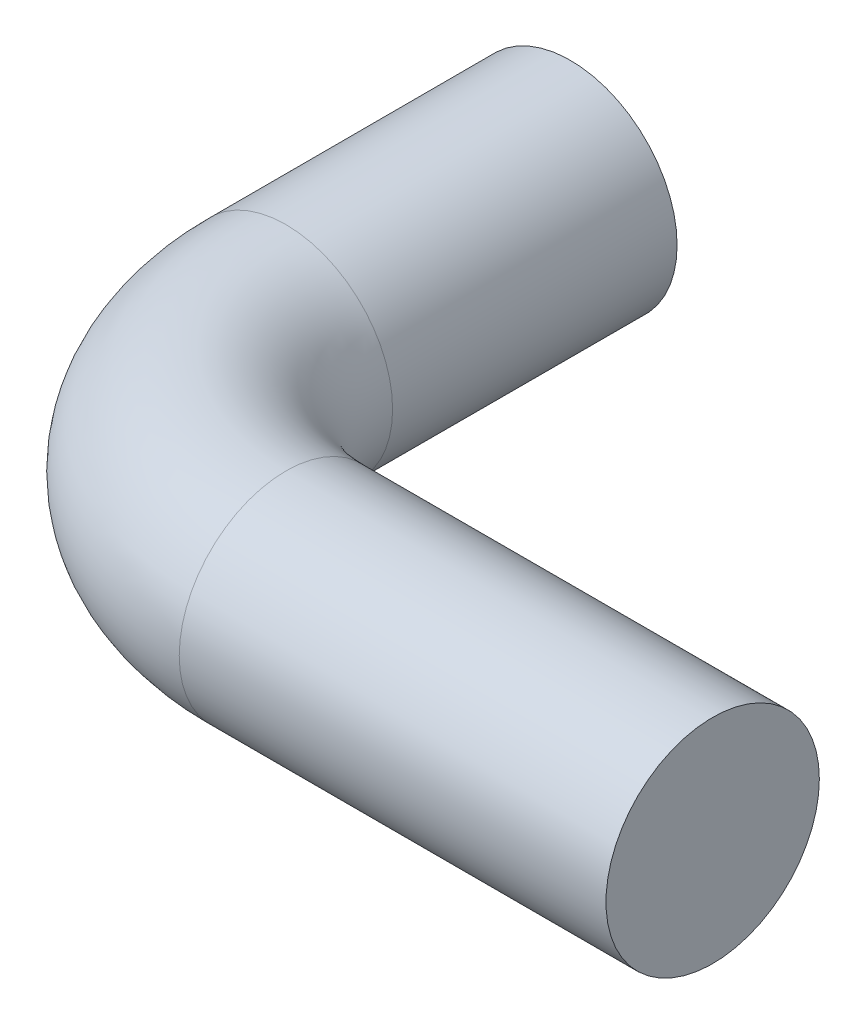
SolidWorks part; units mm, degrees
ref_plane "Front Plane" through (0, 0, 0) normal (0, 0, 1) x (1, 0, 0)
ref_plane "Top Plane" through (0, 0, 0) normal (0, 1, 0) x (1, 0, 0)
ref_plane "Right Plane" through (0, 0, 0) normal (1, 0, 0) x (0, 0, -1)
sketch "Sketch2" plane through (0, 0, 0) normal (0, 1, 0) x (1, 0, 0)
  line L0 (0, 0) -> (150, 0)
  line L1 (-75, 175) -> (-75, 75)
  arc A0 (-75, 75) -> (0, 0) centre (0, 75) ccw
  dimension "150" = 150
  dimension "D2" = 75
  dimension "D3" = 75
  dimension "D4" = 100
sketch "Sketch3" plane through (0, 0, 0) normal (1, 0, 0) x (0, 0, -1)
  circle A0 centre (0, 0) radius 37.5
  dimension "D1" = 75
sweep "Sweep1" add path "Sketch2" circular profile diameter 75 parameters "D3"=75
